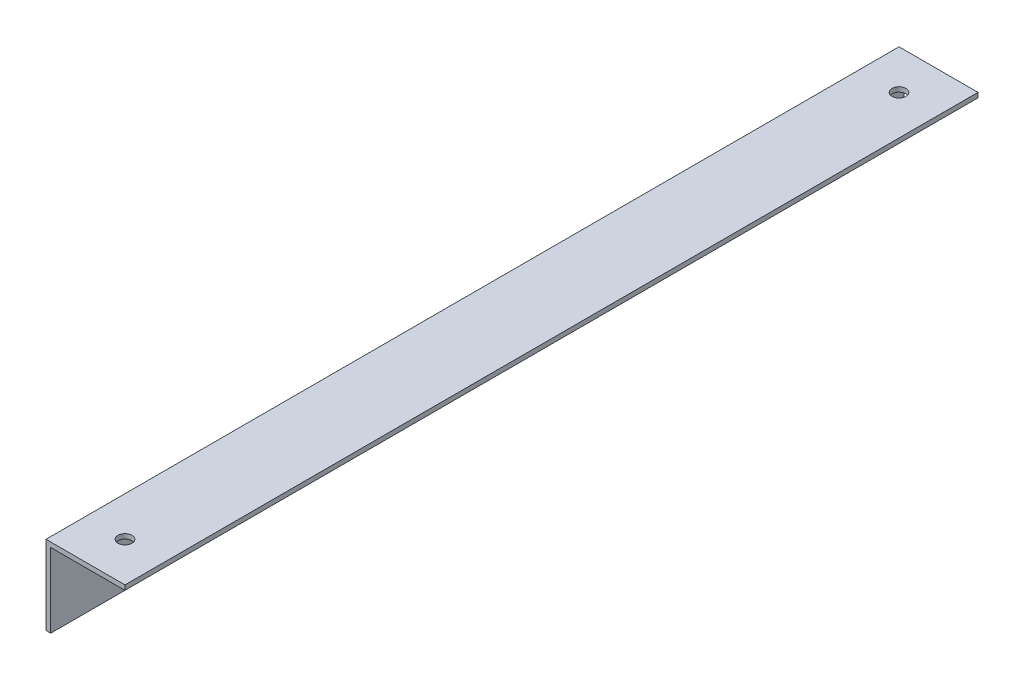
SolidWorks part; units mm, degrees
ref_plane "Front" through (0, 0, 0) normal (0, 0, 1) x (1, 0, 0)
ref_plane "Top" through (0, 0, 0) normal (0, 1, 0) x (1, 0, 0)
ref_plane "Right" through (0, 0, 0) normal (1, 0, 0) x (0, 0, -1)
sketch "Эскиз1" plane through (0, 0, 0) normal (0, 0, 1) x (1, 0, 0)
  line L0 (0, 0) -> (0, -25)
  line L1 (0, 0) -> (25, 0)
  line L2 (0, -25) -> (1.5, -25)
  line L3 (1.5, -25) -> (1.5, -1.5)
  line L4 (1.5, -1.5) -> (25, -1.5)
  line L5 (25, -1.5) -> (25, 0)
  dimension "D1" = 25
  dimension "D2" = 25
  dimension "D3" = 1.5
  dimension "D4" = 1.5
extrude "Бобышка-Вытянуть1" add sketch "Эскиз1" along normal blind 270
sketch "Эскиз2" plane through (0, 0, 0) normal (0, 1, 0) x (1, 0, 0)
  line L0 (12.5, 0) -> (12.5, -270) construction
  line L1 (25, 0) -> (0, 0) construction
  line L2 (25, -270) -> (0, -270) construction
  circle A0 centre (12.5, -257.5) radius 2.2
  circle A1 centre (12.5, -12.5) radius 2.2
  dimension "D1" = 12.5
  dimension "D2" = 12.5
extrude "Вырез-Вытянуть1" cut sketch "Эскиз2" against normal up to next
